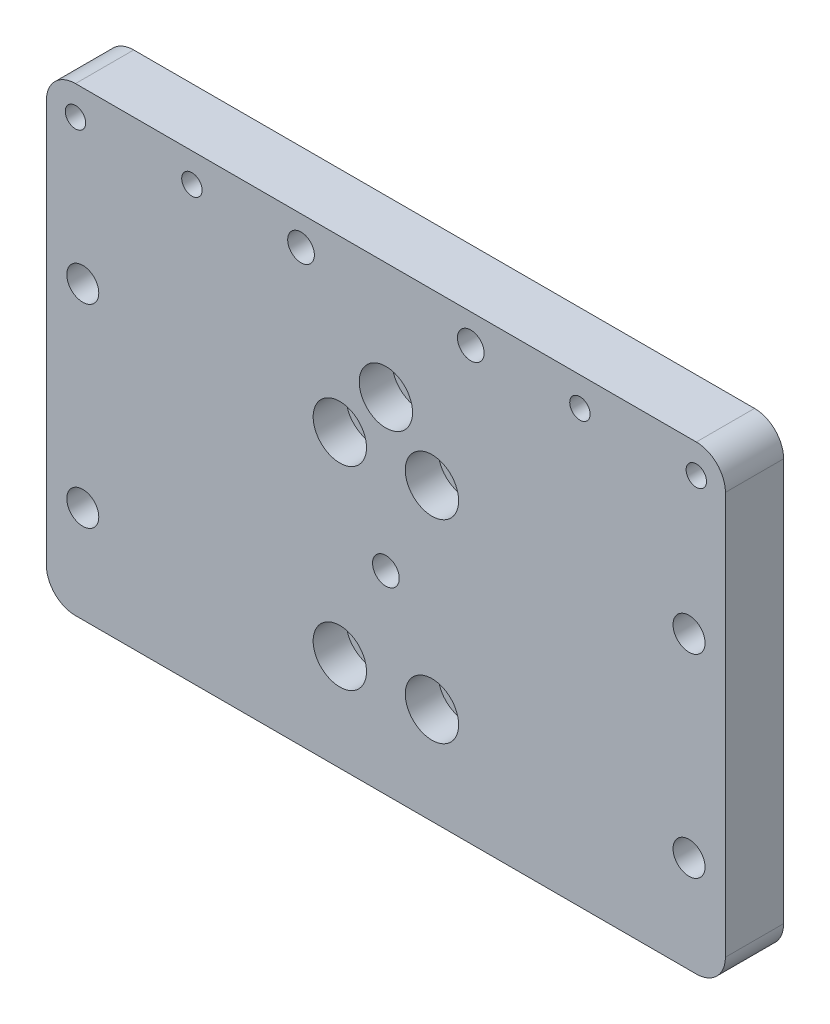
SolidWorks part; units mm, degrees
material "1060 Alloy"
ref_plane "Front Plane" through (0, 0, 0) normal (0, 0, 1) x (1, 0, 0)
ref_plane "Top Plane" through (0, 0, 0) normal (0, 1, 0) x (1, 0, 0)
ref_plane "Right Plane" through (0, 0, 0) normal (1, 0, 0) x (0, 0, -1)
sketch "Sketch1" plane through (0, 0, 0) normal (0, 0, 1) x (1, 0, 0)
  line L1 (70, -47.5) -> (-70, -47.5)
  line L2 (70, -47.5) -> (70, 47.5)
  line L3 (70, 47.5) -> (-70, 47.5)
  line L4 (-70, -47.5) -> (-70, 47.5)
  line L5 (70, -47.5) -> (-70, 47.5) construction
  line L6 (70, 47.5) -> (-70, -47.5) construction
  point P0 (0, 0)
  dimension "D1" = 140
  dimension "D2" = 95
extrude "Boss-Extrude1" add sketch "Sketch1" along normal mid plane 12
sketch "Sketch2" plane through (0, 0, 6) normal (0, 0, 1) x (1, 0, 0)
  line L0 (0, 74.5662) -> (0, 4.4431) construction
  line L1 (-70, -47.5) -> (70, -47.5) construction
  line L2 (-9.5, 12.5) -> (-9.5, -27.5) construction
  line L3 (70, 47.5) -> (-70, 47.5) construction
  line L4 (-64, 41.5) -> (-40, 41.5) construction
  line L5 (-40, 41.5) -> (-17.5, 41.5) construction
  line L6 (-70, 47.5) -> (-70, -47.5) construction
  line L7 (-62.5, 12.5) -> (-62.5, -27.5) construction
  circle A0 centre (0, 23.5) radius 2.75
  circle A1 centre (0, -7.5) radius 2.75
  circle A2 centre (-9.5, 12.5) radius 3.3
  circle A3 centre (-9.5, -27.5) radius 3.3
  circle A4 centre (-17.5, 41.5) radius 2.75
  circle A5 centre (-40, 41.5) radius 2.1
  circle A6 centre (-64, 41.5) radius 2.1
  circle A7 centre (-62.5, 12.5) radius 3.3
  circle A8 centre (-62.5, -27.5) radius 3.3
  circle A9 centre (62.5, -27.5) radius 3.3
  circle A10 centre (62.5, 12.5) radius 3.3
  circle A11 centre (64, 41.5) radius 2.1
  circle A12 centre (40, 41.5) radius 2.1
  circle A13 centre (17.5, 41.5) radius 2.75
  circle A14 centre (9.5, -27.5) radius 3.3
  circle A15 centre (9.5, 12.5) radius 3.3
  dimension "D1" = 6.6
  dimension "D2" = 4.2
  dimension "D3" = 5.5
  dimension "D4" = 40
  dimension "D5" = 20
  dimension "D6" = 19
  dimension "D7" = 35
  dimension "D8" = 24
  dimension "D9" = 6
  dimension "D10" = 24
  dimension "D11" = 22.5
  dimension "D12" = 6
  dimension "D13" = 7.5
  dimension "D14" = 20
  dimension "D15" = 40
extrude "Cut-Extrude1" cut sketch "Sketch2" against normal through all
sketch "Sketch3" plane through (0, 0, 6) normal (0, 0, 1) x (1, 0, 0)
  circle A0 centre (-9.5, -27.5) radius 5.5
  circle A1 centre (9.5, -27.5) radius 5.5
  circle A2 centre (9.5, 12.5) radius 5.5
  circle A3 centre (0, 23.5) radius 5.5
  circle A4 centre (-9.5, 12.5) radius 5.5
  dimension "D1" = 11
extrude "Cut-Extrude2" cut sketch "Sketch3" against normal blind 6.8
fillet "Fillet1" radius 6 4 edges at (70, -47.5, 0) (70, 47.5, 0) (-70, -47.5, 0) (-70, 47.5, 0)
equation "\"M5_tap\"=4.2mm"
equation "\"M5_clearence\"=5.5mm"
equation "\"M6_tap\"=5mm"
equation "\"M6_clearence\"=6.6mm"
equation "\"D1@Sketch2\"=\"M6_clearence\""
equation "\"D2@Sketch2\"=\"M5_tap\""
equation "\"D3@Sketch2\"=\"M5_clearence\""
